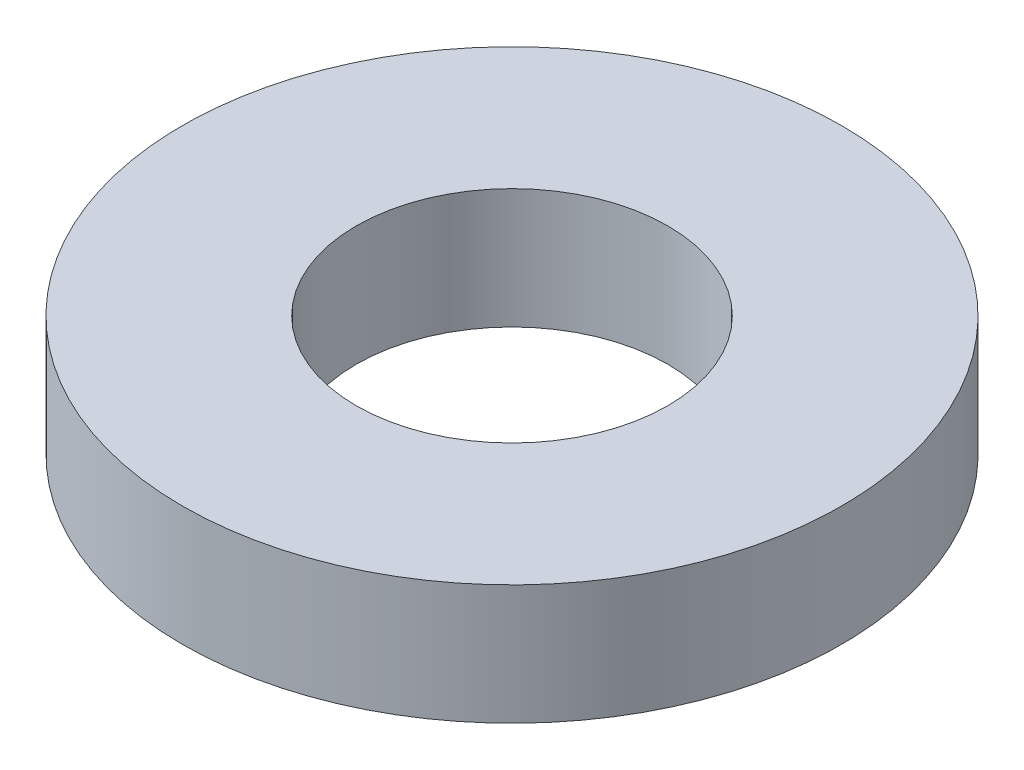
SolidWorks part; units mm, degrees
ref_plane "Plan de face" through (0, 0, 0) normal (0, 0, 1) x (1, 0, 0)
ref_plane "Plan de dessus" through (0, 0, 0) normal (0, 1, 0) x (1, 0, 0)
ref_plane "Plan de droite" through (0, 0, 0) normal (1, 0, 0) x (0, 0, -1)
sketch "Esquisse1" plane through (0, 0, 0) normal (0, 1, 0) x (1, 0, 0)
  circle A0 centre (-26.3222, 4.6017) radius 2.6
  circle A1 centre (-26.3222, 4.6017) radius 5.5
  dimension "D1" = 5.2
  dimension "D2" = 11
extrude "Boss.-Extru.1" add sketch "Esquisse1" along normal blind 2 contours A1
